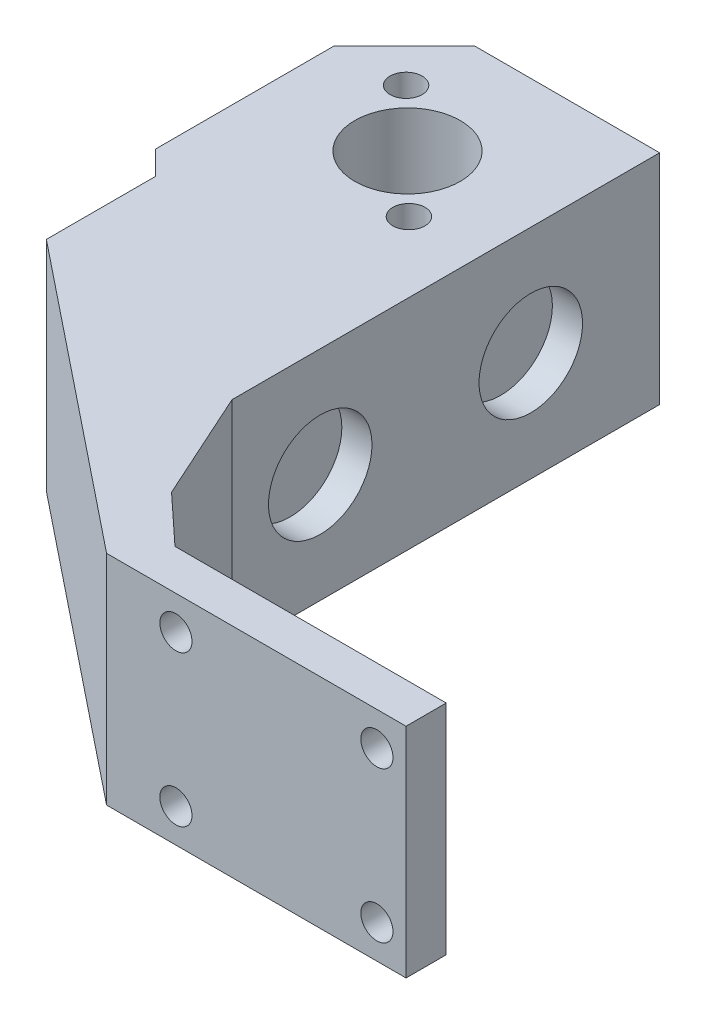
SolidWorks part; units mm, degrees
ref_plane "Přední rovina" through (0, 0, 0) normal (0, 0, 1) x (1, 0, 0)
ref_plane "Horní rovina" through (0, 0, 0) normal (0, 1, 0) x (1, 0, 0)
ref_plane "Pravá rovina" through (0, 0, 0) normal (1, 0, 0) x (0, 0, -1)
sketch "Skica1" plane through (0, 0, 0) normal (0, 0, 1) x (1, 0, 0)
  line L1 (16.212, -19.9414) -> (-9.588, -19.9414)
  line L2 (16.212, -19.9414) -> (16.212, 1.7586)
  line L3 (16.212, 1.7586) -> (-9.588, 1.7586)
  line L4 (-9.588, -19.9414) -> (-9.588, 1.7586)
  circle A0 centre (-6.688, -1.5914) radius 1.6
  circle A1 centre (13.312, -1.5914) radius 1.6
  circle A2 centre (13.312, -16.5914) radius 1.6
  circle A3 centre (-6.688, -16.5914) radius 1.6
  dimension "D1" = 3.2
  dimension "D2" = 2
  dimension "D3" = 2
extrude "Přidat vysunutím1" add sketch "Skica1" along normal blind 4
sketch "Skica2" plane through (-9.588, 0, 0) normal (-1, 0, 0) x (0, 0, 1)
  line L1 (4, -19.9414) -> (0, -19.9414)
  line L2 (4, -19.9414) -> (4, 1.7586)
  line L3 (4, 1.7586) -> (0, 1.7586)
  line L4 (0, -19.9414) -> (0, 1.7586)
extrude "Přidat vysunutím2" add sketch "Skica2" along normal blind 4
sketch "Skica4" plane through (0, 1.7586, 0) normal (0, 1, 0) x (1, 0, 0)
  line L0 (-13.588, -4) -> (-13.588, 0)
  line L1 (-13.588, -4) -> (-43.6402, 20.0598)
  line L3 (-43.6402, 20.0598) -> (-43.6402, 24.0598)
  line L4 (-15.6228, 4.5002) -> (-20.5891, 15.4839)
  line L6 (-43.6402, 20.0598) -> (-43.6402, 30.9081)
  line L7 (-43.6402, 58.0377) -> (-22.6582, 58.0377)
  line L15 (-45.9944, 33.2623) -> (-45.9944, 58.0377)
  line L16 (-45.9944, 58.0377) -> (-20.5891, 58.0377)
  line L17 (-20.5891, 33.2623) -> (-20.5891, 58.0377)
  line L19 (-41.1669, 53.3299) -> (-25.4166, 37.9701) construction
  line L20 (-44.2574, 44.781) -> (-44.2428, 46.6862) construction
  line L21 (-45.9944, 33.2623) -> (-43.6402, 30.9081)
  line L22 (-20.5891, 33.2623) -> (-20.5891, 15.4839)
  line L23 (-10.7834, 0) -> (-15.6228, 4.5002)
  line L24 (16.212, 0) -> (-13.588, 0) construction
  line L25 (-10.7834, 0) -> (-13.588, 0)
  circle A0 centre (-33.2918, 45.65) radius 5.25
  circle A1 centre (-33.2918, 45.65) radius 11 construction
  circle A2 centre (-33.2918, 45.65) radius 8 construction
  circle A3 centre (-39.0192, 51.2354) radius 1.6
  circle A5 centre (-27.5643, 40.0646) radius 1.6
  point P30 (-33.2918, 45.65)
  point P31 (-39.0192, 51.2354)
  point P34 (9.6163, 49.0997)
  point P36 (-33.2918, 45.65)
  dimension "D1" = 10.5
  dimension "D2" = 22
  dimension "D3" = 16
  dimension "D4" = 3.2
  dimension "D5" = 2
extrude "Přidat vysunutím3" add sketch "Skica4" against normal up to surface (21.7 mm away)
chamfer "Zkosení1" distance 7 angle 45 1 edges at (-45.9944, -9.0914, -58.0377)
sketch "Skica5" plane through (-20.5891, 0, 0) normal (1, 0, 0) x (0, 0, -1)
  line L0 (58.0377, -9.0914) -> (15.4839, -9.0914) construction
  line L1 (58.0377, -19.9414) -> (58.0377, 1.7586) construction
  line L2 (15.4839, -19.9414) -> (15.4839, 1.7586) construction
  circle A0 centre (24.2637, -9.0914) radius 5.15
  circle A1 centre (45.2162, -9.0914) radius 5.15
  dimension "D1" = 10.3
extrude "Odebrat vysunutím1" cut sketch "Skica5" against normal blind 3
